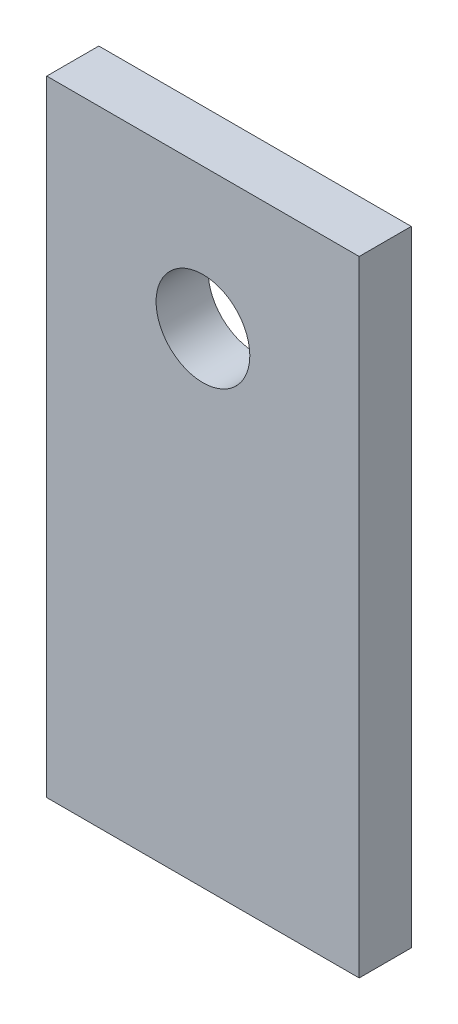
SolidWorks part; units mm, degrees
ref_plane "Płaszczyzna przednia" through (0, 0, 0) normal (0, 0, 1) x (1, 0, 0)
ref_plane "Płaszczyzna górna" through (0, 0, 0) normal (0, 1, 0) x (1, 0, 0)
ref_plane "Płaszczyzna prawa" through (0, 0, 0) normal (1, 0, 0) x (0, 0, -1)
sketch "Szkic2" plane through (0, 0, 0) normal (0, 0, 1) x (1, 0, 0)
  line L2 (0, 0) -> (30, 0)
  line L3 (0, 0) -> (0, 60)
  line L4 (0, 60) -> (30, 60)
  line L5 (30, 0) -> (30, 60)
  circle A0 centre (15, 46.5) radius 4.5
  point P7 (0, 0)
  point P8 (15, 0)
  dimension "D3" = 9
  dimension "D1" = 30
  dimension "D2" = 60
  dimension "D4" = 46.5
extrude "Dodanie-wyciągnięcie1" add sketch "Szkic2" along normal blind 5
